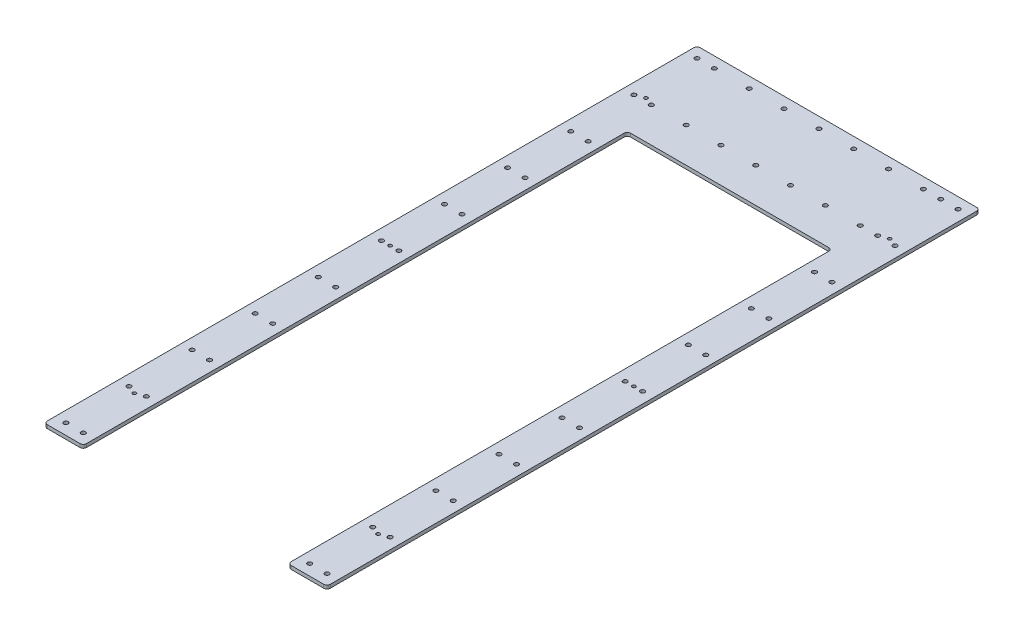
SolidWorks part; units mm, degrees
ref_plane "Front Plane" through (0, 0, 0) normal (0, 0, 1) x (1, 0, 0)
ref_plane "Top Plane" through (0, 0, 0) normal (0, 1, 0) x (1, 0, 0)
ref_plane "Right Plane" through (0, 0, 0) normal (1, 0, 0) x (0, 0, -1)
sketch "Sketch1" plane through (0, 0, 0) normal (0, 1, 0) x (1, 0, 0)
  line L0 (0, 300) -> (0, -300) construction
  line L1 (-130, -300) -> (-94, -300)
  line L2 (-130, -300) -> (-130, 300)
  line L3 (-130, 300) -> (130, 300)
  line L4 (130, -300) -> (130, 300)
  line L5 (-130, -300) -> (130, 300) construction
  line L6 (-130, 300) -> (130, -300) construction
  line L9 (-94, 200) -> (94, 200)
  line L11 (-94, 200) -> (-94, -300)
  line L12 (94, 200) -> (94, -300)
  line L13 (-130, 0) -> (130, 0) construction
  line L18 (94, -300) -> (130, -300)
  line L20 (112, -300) -> (112, 300) construction
  circle A0 centre (120, 290) radius 2
  circle A1 centre (120, 232) radius 2
  circle A2 centre (120, 174) radius 2
  circle A3 centre (120, 116) radius 2
  circle A4 centre (120, 58) radius 2
  circle A5 centre (120, 0) radius 2
  circle A6 centre (120, -58) radius 2
  circle A7 centre (120, -116) radius 2
  circle A8 centre (120, -174) radius 2
  circle A9 centre (120, -232) radius 2
  circle A10 centre (120, -290) radius 2
  circle A11 centre (-120, 232) radius 2
  circle A12 centre (-120, -290) radius 2
  circle A13 centre (-120, -232) radius 2
  circle A14 centre (-120, -174) radius 2
  circle A15 centre (-120, -116) radius 2
  circle A16 centre (-120, -58) radius 2
  circle A17 centre (-120, 0) radius 2
  circle A18 centre (-120, 58) radius 2
  circle A19 centre (-120, 116) radius 2
  circle A20 centre (-120, 174) radius 2
  circle A21 centre (-120, 290) radius 2
  circle A22 centre (112, 235) radius 1.6
  circle A23 centre (-112, 235) radius 1.6
  circle A24 centre (112, -235) radius 1.6
  circle A25 centre (-112, -235) radius 1.6
  circle A26 centre (104, 290) radius 2
  circle A27 centre (104, 232) radius 2
  circle A28 centre (104, 174) radius 2
  circle A29 centre (104, 116) radius 2
  circle A30 centre (104, 58) radius 2
  circle A31 centre (104, 0) radius 2
  circle A32 centre (104, -58) radius 2
  circle A33 centre (104, -116) radius 2
  circle A34 centre (104, -174) radius 2
  circle A35 centre (104, -232) radius 2
  circle A36 centre (104, -290) radius 2
  circle A37 centre (-104, -290) radius 2
  circle A38 centre (-104, -232) radius 2
  circle A39 centre (-104, -174) radius 2
  circle A40 centre (-104, -116) radius 2
  circle A41 centre (-104, -58) radius 2
  circle A42 centre (-104, 0) radius 2
  circle A43 centre (-104, 58) radius 2
  circle A44 centre (-104, 116) radius 2
  circle A45 centre (-104, 174) radius 2
  circle A46 centre (-104, 232) radius 2
  circle A47 centre (-104, 290) radius 2
  circle A49 centre (112, 0) radius 1.6
  circle A50 centre (-112, 0) radius 1.6
  circle A51 centre (-72, 290) radius 2
  circle A52 centre (-40, 290) radius 2
  circle A53 centre (-8, 290) radius 2
  circle A54 centre (24, 290) radius 2
  circle A55 centre (56, 290) radius 2
  circle A56 centre (88, 290) radius 2
  circle A58 centre (-72, 232) radius 2
  circle A59 centre (-40, 232) radius 2
  circle A60 centre (-8, 232) radius 2
  circle A61 centre (24, 232) radius 2
  circle A62 centre (56, 232) radius 2
  circle A63 centre (88, 232) radius 2
  circle A65 centre (120, 290) radius 2 [skipped]
  circle A66 centre (120, 232) radius 2 [skipped]
  point P0 (0, 0)
  point P6 (0, 0)
  dimension "D3" = 4
  dimension "D7" = 3.2
  dimension "D11" = 4
  dimension "D15" = 3.2
  dimension "D1" = 600
  dimension "D2" = 260
  dimension "D4" = 10
  dimension "D5" = 10
  dimension "D9" = 188
  dimension "D12" = 16
  dimension "D10" = 100
  dimension "D14" = 94
  dimension "D8" = 235
  dimension "D6" = 11
  dimension "D13" = 11
  dimension "D16" = 8
  dimension "D17" = 8
extrude "Boss-Extrude1" add sketch "Sketch1" along normal blind 3.175
fillet "Fillet1" radius 3 8 edges at (130, 1.5875, 300) (-130, 1.5875, 300) (130, 1.5875, -300) (-130, 1.5875, -300) (94, 1.5875, 300) (-94, 1.5875, 300) (94, 1.5875, -200) (-94, 1.5875, -200)
equation "\"width\"=260"
equation "\"length\"= 600"
equation "\"D2@Sketch1\"=\"width\""
equation "\"D1@Sketch1\"=\"length\""
equation "\"m3\"= 3.2"
